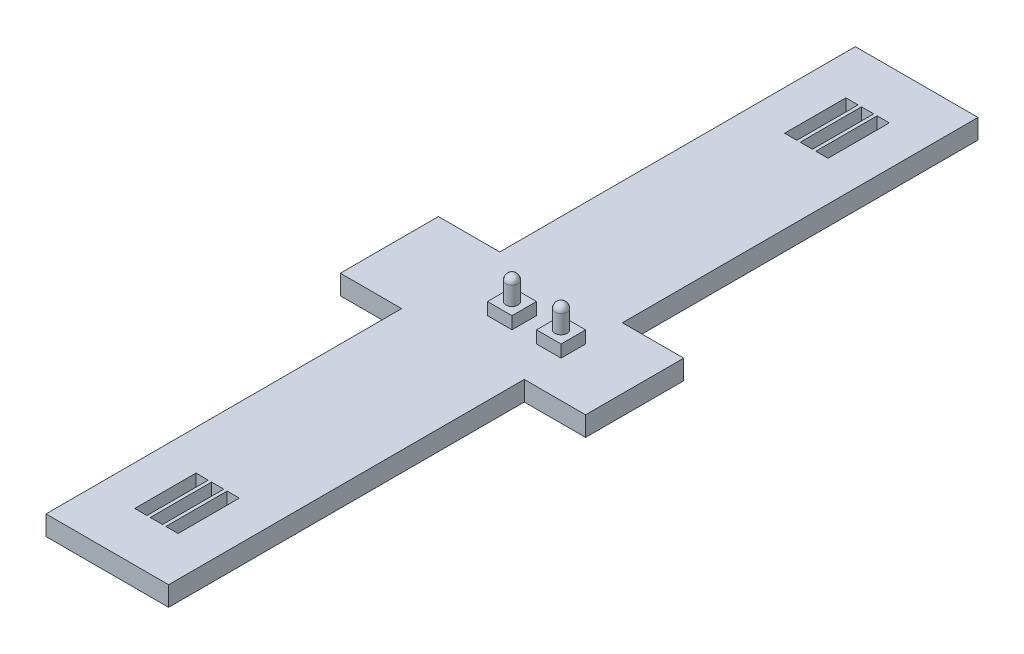
SolidWorks part; units mm, degrees
ref_plane "Front Plane" through (0, 0, 0) normal (0, 0, 1) x (1, 0, 0)
ref_plane "Top Plane" through (0, 0, 0) normal (0, 1, 0) x (1, 0, 0)
ref_plane "Right Plane" through (0, 0, 0) normal (1, 0, 0) x (0, 0, -1)
sketch "Sketch2" plane through (0, 0, 0) normal (0, 1, 0) x (1, 0, 0)
  line L0 (0, 33) -> (0, 0) construction
  line L1 (-5, 33) -> (5, 33)
  line L2 (-5, 33) -> (-5, -33)
  line L3 (-5, 0) -> (5, 0) construction
  line L4 (5, 33) -> (5, -33)
  line L5 (-5, 20) -> (5, 20) construction
  line L8 (-5, -33) -> (5, -33)
  dimension "D1" = 20
  dimension "D2" = 10
  dimension "D3" = 13
extrude "Boss-Extrude1" add sketch "Sketch2" along normal blind 1.6
sketch "Sketch3" plane through (0, 1.6, 0) normal (0, 1, 0) x (1, 0, 0)
  line L0 (-5, 0) -> (5, 0) construction
  line L1 (-5, 33) -> (-5, -33) construction
  line L2 (5, -33) -> (5, 33) construction
  line L39 (0, 33) -> (0, 26.5) construction
  line L40 (5, 33) -> (-5, 33) construction
  line L41 (-5, 26.5) -> (5, 26.5) construction
  line L42 (0.77, 29) -> (1.77, 29)
  line L43 (-0.5, 29) -> (0.5, 29)
  line L44 (-0.5, 29) -> (-0.5, 24)
  line L45 (-0.5, 24) -> (0.5, 24)
  line L46 (0.5, 29) -> (0.5, 24)
  line L47 (-0.5, 29) -> (0.5, 24) construction
  line L48 (-0.5, 24) -> (0.5, 29) construction
  line L49 (0.77, 29) -> (0.77, 24)
  line L50 (0.77, 24) -> (1.77, 24)
  line L51 (1.77, 29) -> (1.77, 24)
  line L52 (0.77, 29) -> (1.77, 24) construction
  line L53 (0.77, 24) -> (1.77, 29) construction
  line L54 (-0.77, 24) -> (-1.77, 29) construction
  line L55 (-0.77, 29) -> (-1.77, 24) construction
  line L56 (-1.77, 29) -> (-1.77, 24)
  line L57 (-0.77, 24) -> (-1.77, 24)
  line L58 (-0.77, 29) -> (-0.77, 24)
  line L59 (-0.77, 29) -> (-1.77, 29)
  line L60 (-0.77, -29) -> (-1.77, -24) construction
  line L61 (-0.77, -24) -> (-1.77, -29) construction
  line L62 (0.77, -24) -> (1.77, -29) construction
  line L63 (0.77, -29) -> (1.77, -24) construction
  line L64 (-0.5, -24) -> (0.5, -29) construction
  line L65 (-0.5, -29) -> (0.5, -24) construction
  line L66 (-5, -26.5) -> (5, -26.5) construction
  line L67 (0, -33) -> (0, -26.5) construction
  line L68 (-0.77, -29) -> (-1.77, -29)
  line L69 (-0.77, -29) -> (-0.77, -24)
  line L70 (-0.77, -24) -> (-1.77, -24)
  line L71 (-1.77, -29) -> (-1.77, -24)
  line L72 (1.77, -29) -> (1.77, -24)
  line L73 (0.77, -24) -> (1.77, -24)
  line L74 (0.77, -29) -> (0.77, -24)
  line L75 (0.5, -29) -> (0.5, -24)
  line L76 (-0.5, -24) -> (0.5, -24)
  line L77 (-0.5, -29) -> (-0.5, -24)
  line L78 (-0.5, -29) -> (0.5, -29)
  line L79 (0.77, -29) -> (1.77, -29)
  point P6 (0, 26.5)
  point P19 (1.27, 26.5)
  point P26 (-1.27, 26.5)
  point P43 (-1.27, -26.5)
  point P44 (1.27, -26.5)
  point P45 (0, -26.5)
  dimension "D4" = 2
  dimension "D1" = 1
  dimension "D2" = 5
  dimension "D3" = 4
extrude "Cut-Extrude1" cut sketch "Sketch3" against normal up to next
sketch "Sketch4" plane through (0, 0, 0) normal (0, -1, 0) x (1, 0, 0)
  line L0 (-5, 0) -> (5, 0) construction
  line L1 (-5, -33) -> (-5, 33) construction
  line L2 (5, 33) -> (5, -33) construction
  line L3 (-10, -4) -> (10, -4)
  line L4 (-10, -4) -> (-10, 4)
  line L5 (10, -4) -> (10, 4)
  line L6 (-10, 4) -> (10, 4)
  line L7 (-10, -4) -> (10, 4) construction
  line L8 (10, -4) -> (-10, 4) construction
  point P7 (0, 0)
  dimension "D1" = 8
  dimension "D2" = 5
extrude "Boss-Extrude2" add sketch "Sketch4" against normal up to surface (1.6 mm away) up to face at (0, 1.6, -26.5)
sketch "Sketch5" plane through (0, 1.6, 0) normal (0, 1, 0) x (1, 0, 0)
  line L0 (0, 4) -> (0, -4) construction
  line L1 (-10, 4) -> (10, 4) construction
  line L2 (-10, 4) -> (-10, -4) construction
  line L3 (-10, -4) -> (10, -4) construction
  line L4 (10, 4) -> (10, -4) construction
  line L5 (-1, 1) -> (-1, -1)
  line L6 (-1, 1) -> (1, 1)
  line L7 (-1, -1) -> (1, -1)
  line L8 (1, 1) -> (1, -1)
  line L9 (-1, 1) -> (1, -1) construction
  line L10 (-1, -1) -> (1, 1) construction
  line L11 (3, 1) -> (3, -1)
  line L12 (3, 1) -> (5, 1)
  line L13 (3, -1) -> (5, -1)
  line L14 (5, 1) -> (5, -1)
  line L15 (3, 1) -> (5, -1) construction
  line L16 (3, -1) -> (5, 1) construction
  point P9 (0, 0)
  point P11 (4, 0)
  dimension "D1" = 2
  dimension "D2" = 2
  dimension "D3" = 2
extrude "Boss-Extrude3" add sketch "Sketch5" along normal blind 1
sketch "Sketch6" plane through (0, 2.6, 0) normal (0, 1, 0) x (1, 0, 0)
  line L0 (-1, 1) -> (1, -1) construction
  line L1 (3, 1) -> (5, -1) construction
  circle A0 centre (0, 0) radius 0.5
  circle A1 centre (4, 0) radius 0.5
  dimension "D1" = 1
  dimension "D2" = 2
extrude "Boss-Extrude4" add sketch "Sketch6" along normal blind 2
fillet "Fillet1" radius 0.5 2 edges at (0, 4.6, 0.5) (4, 4.6, 0.5)
